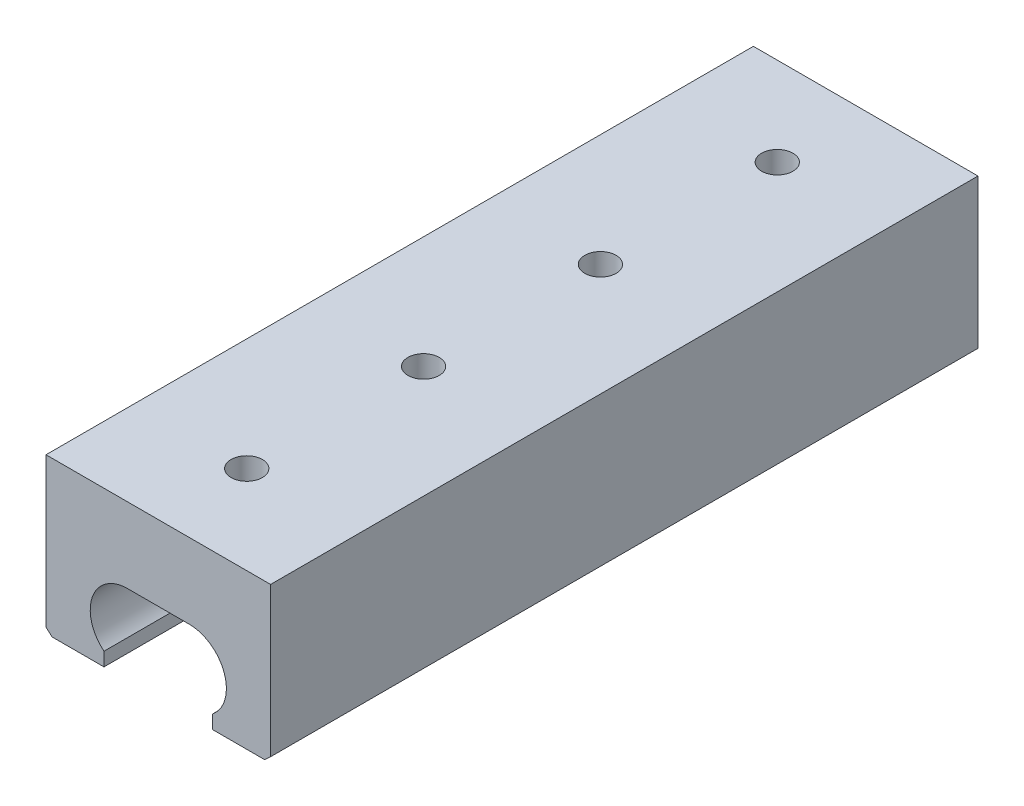
SolidWorks part; units mm, degrees
ref_plane "Front" through (0, 0, 0) normal (0, 0, 1) x (1, 0, 0)
ref_plane "Top" through (0, 0, 0) normal (0, 1, 0) x (1, 0, 0)
ref_plane "Right" through (0, 0, 0) normal (1, 0, 0) x (0, 0, -1)
other "Configuration Table"
sketch "Sketch1" plane through (0, 0, 0) normal (0, 0, 1) x (1, 0, 0)
  line L0 (-51.8484, -29.0299) -> (-51.8484, -32.937)
  line L1 (-68.5064, 11.513) -> (-3.9904, 11.513)
  line L2 (-20.6484, -29.0299) -> (-20.6484, -32.937)
  line L3 (-51.8484, -32.937) -> (-66.7991, -32.937)
  line L5 (-36.2484, 11.513) -> (-36.2484, -41.6818) construction
  line L6 (-45.1384, -10.0684) -> (-27.3584, -10.0684)
  line L7 (-3.9904, 11.513) -> (-3.9904, -31.3555)
  line L8 (-68.5064, 11.513) -> (-68.5064, -31.3555)
  line L9 (-20.6484, -32.937) -> (-5.6976, -32.937)
  line L11 (-68.5064, -31.3555) -> (-66.7991, -32.937)
  line L12 (-3.9904, -31.3555) -> (-5.6976, -32.937)
  arc A1 (-27.3584, -10.0684) -> (-20.6484, -29.0299) centre (-27.3584, -20.7364) cw
  arc A2 (-45.1384, -10.0684) -> (-51.8484, -29.0299) centre (-45.1384, -20.7364) ccw
  point P12 (-36.2484, -10.0684)
  dimension "D6" = 10.668
  dimension "D1" = 44.45
  dimension "D3" = 64.516
  dimension "D5" = 17.78
extrude "Base-Extrude" add sketch "Sketch1" along normal blind 203.2
sketch "Sketch2" plane through (0, 11.513, 0) normal (0, 1, 0) x (-1, 0, 0)
  circle A0 centre (36.2484, 177.8) radius 5.5 construction
  circle A1 centre (36.2484, 177.8) radius 5.5 construction
hole_wizard "Tap Drill for M10x1.0 Tap2" positions "Sketch4" profile "Sketch3" hole size "M10x1.0" standard "Ansi Metric" end condition through all
sketch "Sketch4" plane through (0, 11.513, 0) normal (0, 1, 0) x (-1, 0, 0)
  point P0 (36.2484, 177.8)
sketch "Sketch3" plane through (-36.2484, 11.513, 177.8) normal (1, 0, 0) x (0, 0, 1)
  line L0 (0, 0) -> (0, 44.45)
  line L1 (0, 44.45) -> (4.5, 44.45)
  line L2 (4.5, 44.45) -> (4.5, 0)
  line L5 (4.5, 0) -> (0, 0)
  line L11 (0, -6.35) -> (0, 107.95) construction
  dimension "Thru Hole Dia." = 9
  dimension "Thru Hole Depth" = 44.45
pattern_linear "LPattern1" count 4 spacing 50.8 along (0, 0, -1) of "Tap Drill for M10x1.0 Tap2"
sketch "Sketch5" [suppressed] plane through (0, 11.513, 0) normal (0, 1, 0) x (-1, 0, 0)
  circle A0 centre (36.2484, 177.8) radius 5.5 construction
  circle A1 centre (36.2484, 177.8) radius 5.5 construction
hole_wizard "Tap Drill for M10x1.0 Tap1" [suppressed] positions "Sketch7" profile "Sketch6" hole size "M10x1.0" standard "Ansi Metric"
sketch "Sketch7" plane through (0, 11.513, 0) normal (0, 1, 0) x (-1, 0, 0)
  point P0 (36.2484, 177.8)
sketch "Sketch6" plane through (-36.2484, 11.513, 177.8) normal (1, 0, 0) x (0, 0, 1)
  line L0 (0, 0) -> (0, 44.45)
  line L1 (0, 44.45) -> (4.5, 44.45)
  line L2 (4.5, 44.45) -> (4.5, 0)
  line L5 (4.5, 0) -> (0, 0)
  line L11 (0, -6.35) -> (0, 107.95) construction
  dimension "Thru Hole Dia." = 9
  dimension "Thru Hole Depth" = 44.45
pattern_linear "LPattern2" [suppressed] count 4 spacing 50.8
